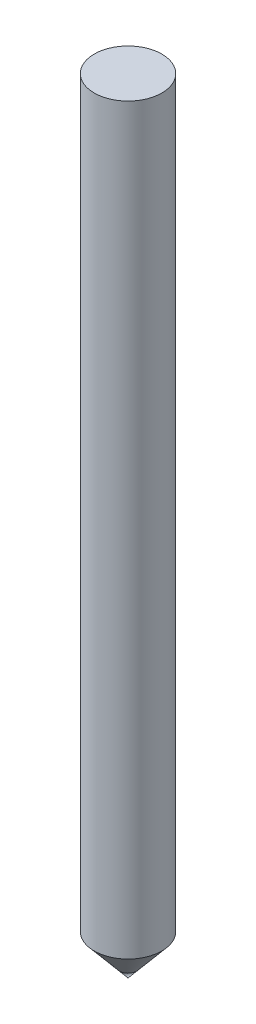
SolidWorks part; units mm, degrees
ref_plane "Front Plane" through (0, 0, 0) normal (0, 0, 1) x (1, 0, 0)
ref_plane "Top Plane" through (0, 0, 0) normal (0, 1, 0) x (1, 0, 0)
ref_plane "Right Plane" through (0, 0, 0) normal (1, 0, 0) x (0, 0, -1)
sketch "Sketch1" plane through (0, 0, 0) normal (0, 1, 0) x (1, 0, 0)
  circle A0 centre (0, 0) radius 5
  dimension "D1" = 10
extrude "Boss-Extrude1" add sketch "Sketch1" along normal blind 110
sketch "Sketch2" plane through (0, 0, 0) normal (0, -1, 0) x (1, 0, 0)
  circle A0 centre (0, 0) radius 5
  dimension "D1" = 10
extrude "Boss-Extrude2" add sketch "Sketch2" along normal blind 50 draft 40
